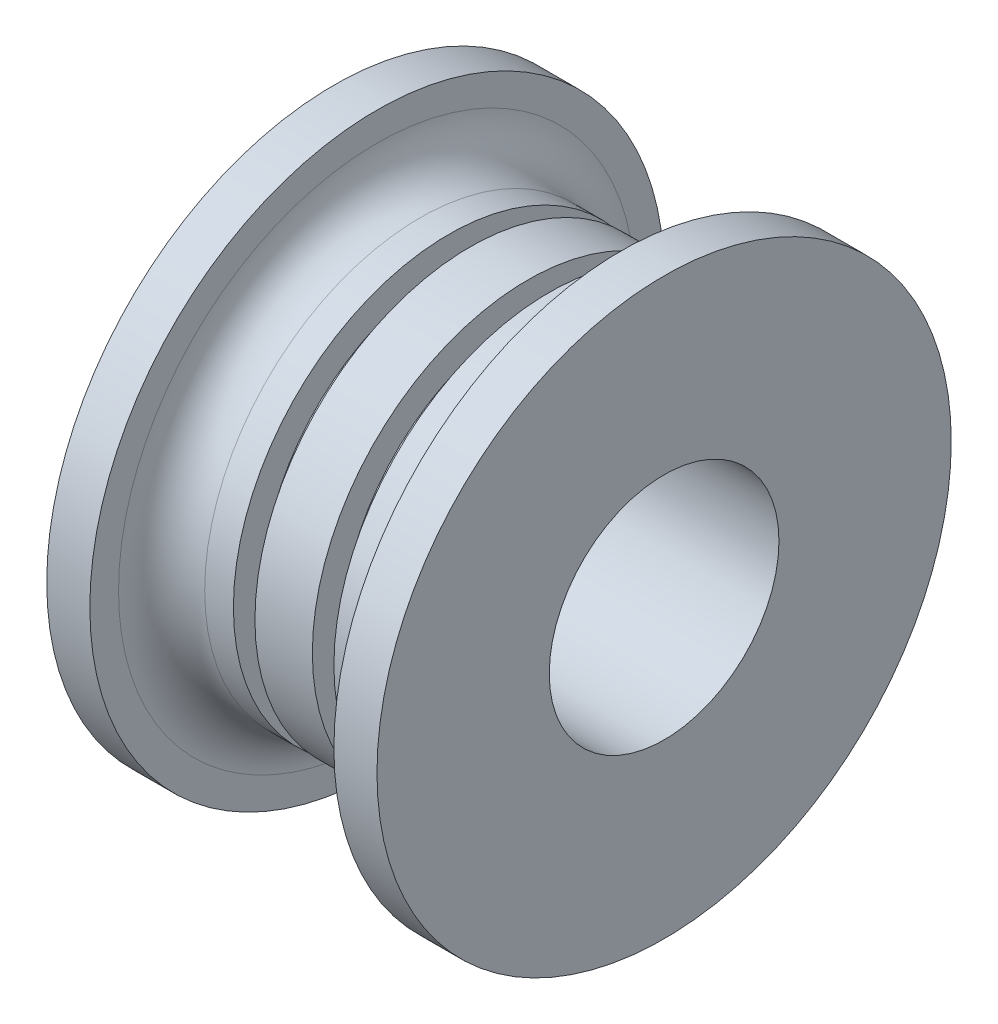
SolidWorks part; units mm, degrees
material "Commercialement pur CP-Ti UNS R50400 (SS)"
ref_plane "Plan de face" through (0, 0, 0) normal (0, 0, 1) x (1, 0, 0)
ref_plane "Plan de dessus" through (0, 0, 0) normal (0, 1, 0) x (1, 0, 0)
ref_plane "Plan de droite" through (0, 0, 0) normal (1, 0, 0) x (0, 0, -1)
sketch "Esquisse2" plane through (0, 0, 0) normal (0, 0, 1) x (1, 0, 0)
  line L0 (0, 200) -> (30, 200) construction
  line L1 (0, 0) -> (265, 0)
  line L9 (0, 150) -> (80, 150) construction
  line L10 (0, 200) -> (0, 80)
  line L11 (230, 200) -> (230, 80)
  line L12 (0, 200) -> (30, 200)
  line L13 (230, 200) -> (200, 200)
  line L14 (135, 150) -> (95, 150)
  line L15 (0, 200) -> (0, 80)
  line L17 (80, 150) -> (80, 130)
  line L18 (80, 130) -> (95, 130)
  line L19 (95, 150) -> (95, 130)
  line L21 (150, 150) -> (150, 130)
  line L22 (150, 130) -> (135, 130)
  line L23 (135, 150) -> (135, 130)
  line L24 (0, 80) -> (230, 80)
  line L25 (95, 150) -> (135, 150) construction
  line L26 (150, 150) -> (265, 150) construction
  line L27 (80, 200) -> (150, 200) construction
  line L29 (30, 200) -> (30, 180)
  line L30 (60, 150) -> (80, 150)
  line L32 (150, 150) -> (170, 150)
  line L35 (200, 180) -> (200, 200)
  line L36 (200, 200) -> (230, 200) construction
  arc A0 (30, 180) -> (60, 150) centre (60, 180) ccw
  arc A1 (170, 150) -> (200, 180) centre (170, 180) ccw
  point P25 (30, 150)
  dimension "D5" = 30
  dimension "D14" = 30
  dimension "D1" = 80
  dimension "D2" = 50
  dimension "D3" = 30
  dimension "D4" = 120
  dimension "D6" = 30
  dimension "D7" = 70
  dimension "D8" = 50
  dimension "D9" = 50
  dimension "D10" = 20
  dimension "D11" = 20
  dimension "D12" = 15
  dimension "D13" = 15
revolve "Révolution1" add sketch "Esquisse2" angle 360 about L1
